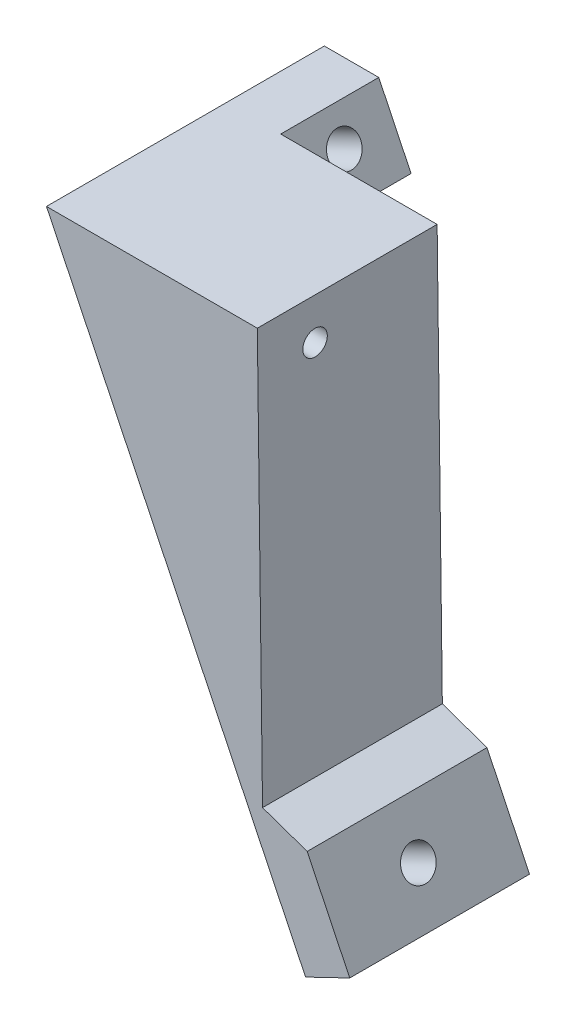
SolidWorks part; units mm, degrees
material "ABS"
ref_plane "Front Plane" through (0, 0, 0) normal (0, 0, 1) x (1, 0, 0)
ref_plane "Top Plane" through (0, 0, 0) normal (0, 1, 0) x (1, 0, 0)
ref_plane "Right Plane" through (0, 0, 0) normal (1, 0, 0) x (0, 0, -1)
sketch "Sketch1" plane through (0, 0, 0) normal (0, 0, 1) x (1, 0, 0)
  line L0 (-36.2386, 24.2413) -> (-9.7428, -30.7587)
  line L1 (-9.7428, -30.7587) -> (-10.436, 24.2413)
  line L2 (-10.436, 24.2413) -> (-36.2386, 24.2413)
  dimension "D1" = 55
  dimension "D2" = 55
  dimension "D3" = 25
extrude "Boss-Extrude1" add sketch "Sketch1" along normal blind 22
sketch "Sketch6" plane through (-19.9343, -9.6032, 0) normal (-0.9009, -0.434, 0) x (0, 0, 1)
  line L0 (22, 37.5671) -> (22, -23.4823) construction
  line L1 (0, 37.5671) -> (-12, 37.5671)
  line L2 (0, 37.5671) -> (0, 25.5671)
  line L3 (0, 25.5671) -> (-12, 25.5671)
  line L4 (-12, 37.5671) -> (-12, 25.5671)
  line L5 (0, -23.4823) -> (22, -23.4823)
  line L6 (0, -23.4823) -> (0, -35.4823)
  line L7 (0, -35.4823) -> (22, -35.4823)
  line L8 (22, -23.4823) -> (22, -35.4823)
  dimension "D1" = 12
  dimension "D2" = 12
  dimension "D3" = 0
  dimension "D4" = 12
extrude "Boss-Extrude4" add sketch "Sketch6" against normal blind 6
sketch "Sketch8" plane through (0, 0, 0) normal (0, 0, -1) x (-1, 0, 0)
  line L0 (9.7428, -30.7587) -> (4.3373, -28.1546)
  line L1 (4.3373, -28.1546) -> (9.7996, -26.2474)
  line L2 (9.7428, -30.7587) -> (10.436, 24.2413) construction
  line L3 (9.7996, -26.2474) -> (9.7428, -30.7587)
extrude "Boss-Extrude5" add sketch "Sketch8" against normal up to vertex (22 mm away)
sketch "Sketch9" plane through (-14.5288, -6.9992, 0) normal (0.9009, 0.434, 0) x (0, 0, -1)
  line L2 (12, 25.5671) -> (0, 25.5671) construction
  line L3 (0, -35.4823) -> (-22, -35.4823) construction
  line L4 (-22, -35.4823) -> (-22, -23.4823) construction
  circle A0 centre (6, 30.5671) radius 2
  circle A1 centre (-11, -29.4823) radius 2
  point P9 (6, 25.5671)
  point P12 (-11, -35.4823)
  point P15 (-22, -29.4823)
  dimension "D1" = 4
  dimension "D2" = 4
  dimension "D3" = 5
  dimension "D4" = 0
  dimension "D5" = 0
  dimension "D6" = 0
extrude "Cut-Extrude9" cut sketch "Sketch9" against normal blind 6
sketch "Sketch10" plane through (-10.1288, -0.1277, 0) normal (0.9999, 0.0126, 0) x (0, 0, -1)
  line L0 (-22, 24.3709) -> (0, 24.3709) construction
  line L2 (-22, -26.1218) -> (-22, 24.3709) construction
  circle A0 centre (-15, 19.3709) radius 1.5
  point P6 (0, 0)
  dimension "D1" = 3
  dimension "D2" = 5
  dimension "D3" = 7
extrude "Cut-Extrude10" cut sketch "Sketch10" against normal blind 36
sketch "Sketch11" plane through (0, 0, 0) normal (0, 0, 1) x (1, 0, 0)
  line L0 (-36.2386, 24.2413) -> (-29.5787, 24.2413)
  line L1 (-29.5787, 24.2413) -> (-30.8332, 26.8454)
  line L2 (-30.8332, 26.8454) -> (-36.2386, 24.2413)
extrude "Cut-Extrude11" cut sketch "Sketch11" against normal blind 36
